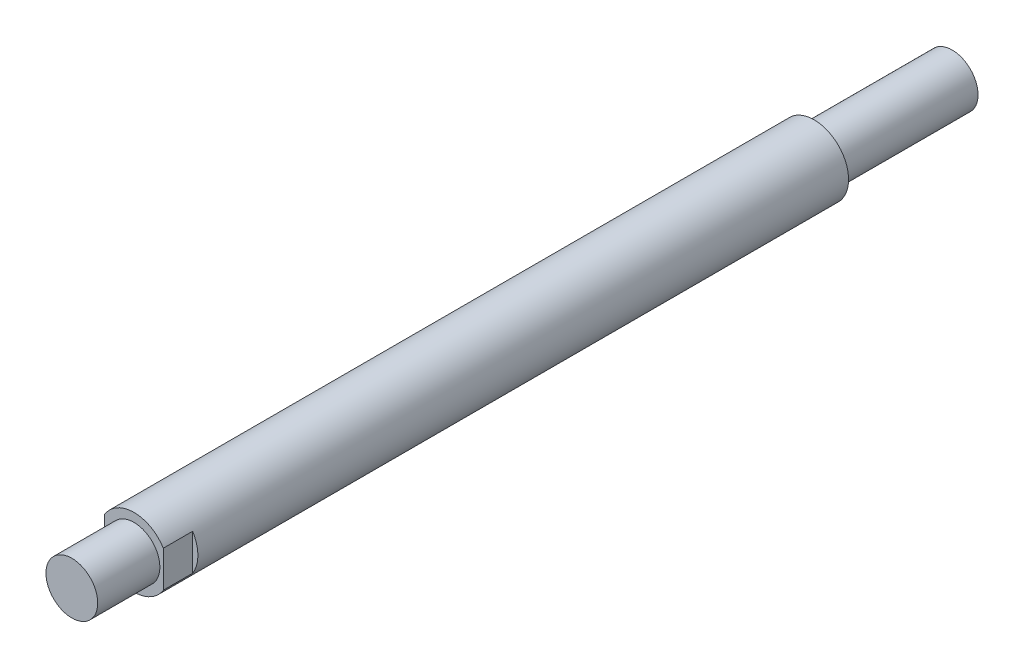
SolidWorks part; units mm, degrees
ref_plane "Front Plane" through (0, 0, 0) normal (0, 0, 1) x (1, 0, 0)
ref_plane "Top Plane" through (0, 0, 0) normal (0, 1, 0) x (1, 0, 0)
ref_plane "Right Plane" through (0, 0, 0) normal (1, 0, 0) x (0, 0, -1)
sketch "Sketch1" plane through (0, 0, 0) normal (0, 0, 1) x (1, 0, 0)
  circle A0 centre (0, 0) radius 20
  dimension "D1" = 40
extrude "Boss-Extrude1" add sketch "Sketch1" along normal mid plane 510
sketch "Sketch2" plane through (0, 0, 255) normal (0, 0, 1) x (1, 0, 0)
  circle A0 centre (0, 0) radius 15
  circle A1 centre (0, 0) radius 20 construction
  circle A2 centre (0, 0) radius 20
  dimension "D1" = 30
extrude "Cut-Extrude1" cut sketch "Sketch2" against normal blind 36
cosmetic thread "Cosmetic Thread1" parameters "D2"=27.797
sketch "Sketch3" plane through (0, 0, 219) normal (0, 0, 1) x (1, 0, 0)
  line L1 (-26.9244, 28.2906) -> (-17, 28.2906)
  line L2 (-26.9244, 28.2906) -> (-26.9244, -22.1786)
  line L3 (-26.9244, -22.1786) -> (-17, -22.1786)
  line L4 (-17, 28.2906) -> (-17, -22.1786)
  line L5 (-26.9244, 28.2906) -> (-17, -22.1786) construction
  line L6 (-26.9244, -22.1786) -> (-17, 28.2906) construction
  line L7 (17, 23.4495) -> (31.0394, 23.4495)
  line L8 (17, 23.4495) -> (17, -22.1786)
  line L9 (17, -22.1786) -> (31.0394, -22.1786)
  line L10 (31.0394, 23.4495) -> (31.0394, -22.1786)
  line L11 (17, 23.4495) -> (31.0394, -22.1786) construction
  line L12 (17, -22.1786) -> (31.0394, 23.4495) construction
  point P0 (-21.9622, 3.056)
  point P5 (24.0197, 0.6354)
  dimension "D1" = 50.4693
  dimension "D2" = 34
  dimension "D3" = 17
extrude "Cut-Extrude2" cut sketch "Sketch3" against normal blind 17
sketch "Sketch4" plane through (0, 0, -255) normal (0, 0, -1) x (-1, 0, 0)
  circle A0 centre (0, 0) radius 15
  circle A1 centre (0, 0) radius 20 construction
  circle A2 centre (0, 0) radius 20
  dimension "D1" = 30
extrude "Cut-Extrude4" cut sketch "Sketch4" against normal blind 80
cosmetic thread "Cosmetic Thread2" parameters "D2"=27.797
